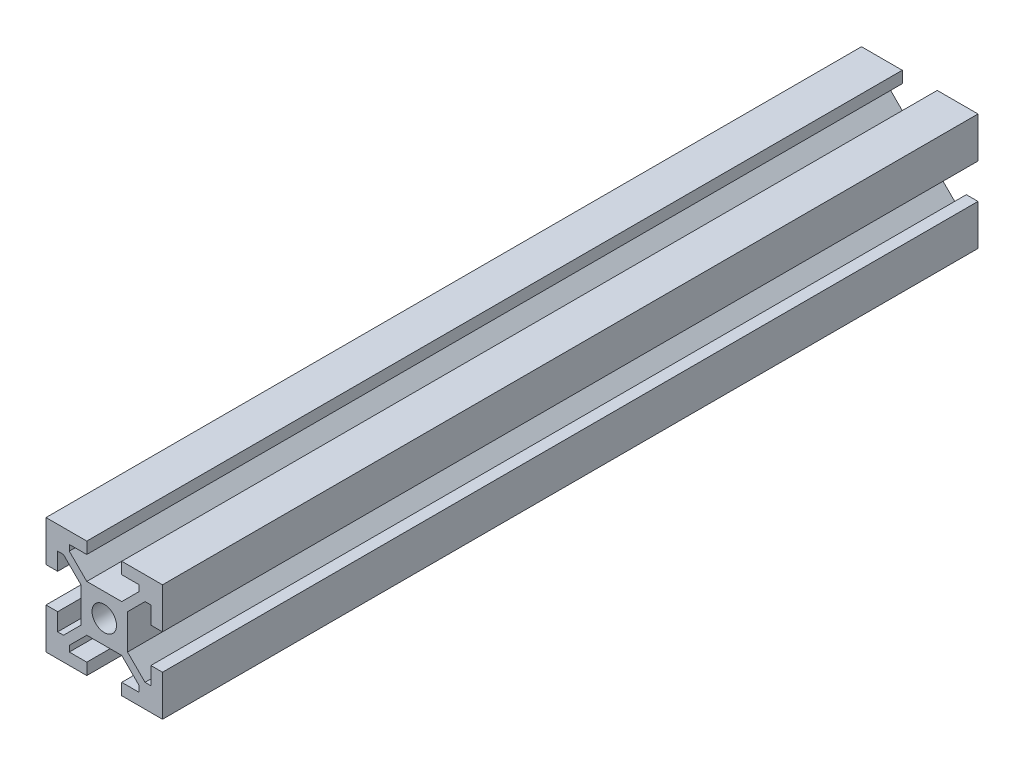
SolidWorks part; units mm, degrees
ref_plane "正面" through (0, 0, 0) normal (0, 0, 1) x (1, 0, 0)
ref_plane "平面" through (0, 0, 0) normal (0, 1, 0) x (1, 0, 0)
ref_plane "右側面" through (0, 0, 0) normal (1, 0, 0) x (0, 0, -1)
sketch "ｽｹｯﾁ2" plane through (0, 0, 0) normal (0, 0, 1) x (1, 0, 0)
  line L0 (0, 0) -> (0, 10) construction
  line L1 (-10, -10) -> (10, -10) construction
  line L2 (-10, -10) -> (-10, 10) construction
  line L3 (-10, 10) -> (10, 10) construction
  line L4 (10, -10) -> (10, 10) construction
  line L5 (-10, -10) -> (10, 10) construction
  line L6 (-10, 10) -> (10, -10) construction
  line L8 (3, 4) -> (-3, 4)
  line L9 (-6, 7) -> (6, 7) construction
  line L10 (-6, 8) -> (-6, 7)
  line L11 (6, 8) -> (6, 7)
  line L12 (-6, 7) -> (-3, 4)
  line L13 (3, 4) -> (6, 7)
  line L14 (-6, 8) -> (-3, 8)
  line L15 (-3, 8) -> (-3, 10)
  line L16 (-3, 10) -> (-10, 10)
  line L17 (6, 8) -> (3, 8)
  line L18 (3, 8) -> (3, 10)
  line L19 (3, 10) -> (10, 10)
  line L20 (7, 6) -> (4, 3)
  line L21 (4, -3) -> (4, 3)
  line L22 (4, -3) -> (7, -6)
  line L23 (8, -6) -> (8, -3)
  line L24 (8, -6) -> (7, -6)
  line L25 (8, -3) -> (10, -3)
  line L26 (10, -3) -> (10, -10)
  line L27 (8, 3) -> (10, 3)
  line L28 (10, 3) -> (10, 10)
  line L29 (8, 6) -> (8, 3)
  line L30 (8, 6) -> (7, 6)
  line L31 (6, -7) -> (3, -4)
  line L32 (-3, -4) -> (3, -4)
  line L33 (-3, -4) -> (-6, -7)
  line L34 (-6, -8) -> (-3, -8)
  line L35 (-6, -8) -> (-6, -7)
  line L36 (-3, -8) -> (-3, -10)
  line L37 (-3, -10) -> (-10, -10)
  line L38 (3, -8) -> (3, -10)
  line L39 (3, -10) -> (10, -10)
  line L40 (6, -8) -> (3, -8)
  line L41 (6, -8) -> (6, -7)
  line L42 (-7, -6) -> (-4, -3)
  line L43 (-4, 3) -> (-4, -3)
  line L44 (-4, 3) -> (-7, 6)
  line L45 (-8, 6) -> (-8, 3)
  line L46 (-8, 6) -> (-7, 6)
  line L47 (-8, 3) -> (-10, 3)
  line L48 (-10, 3) -> (-10, 10)
  line L49 (-8, -3) -> (-10, -3)
  line L50 (-10, -3) -> (-10, -10)
  line L51 (-8, -6) -> (-8, -3)
  line L52 (-8, -6) -> (-7, -6)
  circle A0 centre (0, 0) radius 2.1
  point P0 (0, 0)
  point P11 (0, 10)
  point P14 (0, 4)
  point P17 (0, 7)
  dimension "D8" = 4.2
  dimension "D1" = 20
  dimension "D2" = 6
  dimension "D3" = 2
  dimension "D4" = 4
  dimension "D5" = 12
  dimension "D6" = 6
  dimension "D7" = 4
extrude "ﾎﾞｽ - 押し出し1" add sketch "ｽｹｯﾁ2" along normal blind 140
